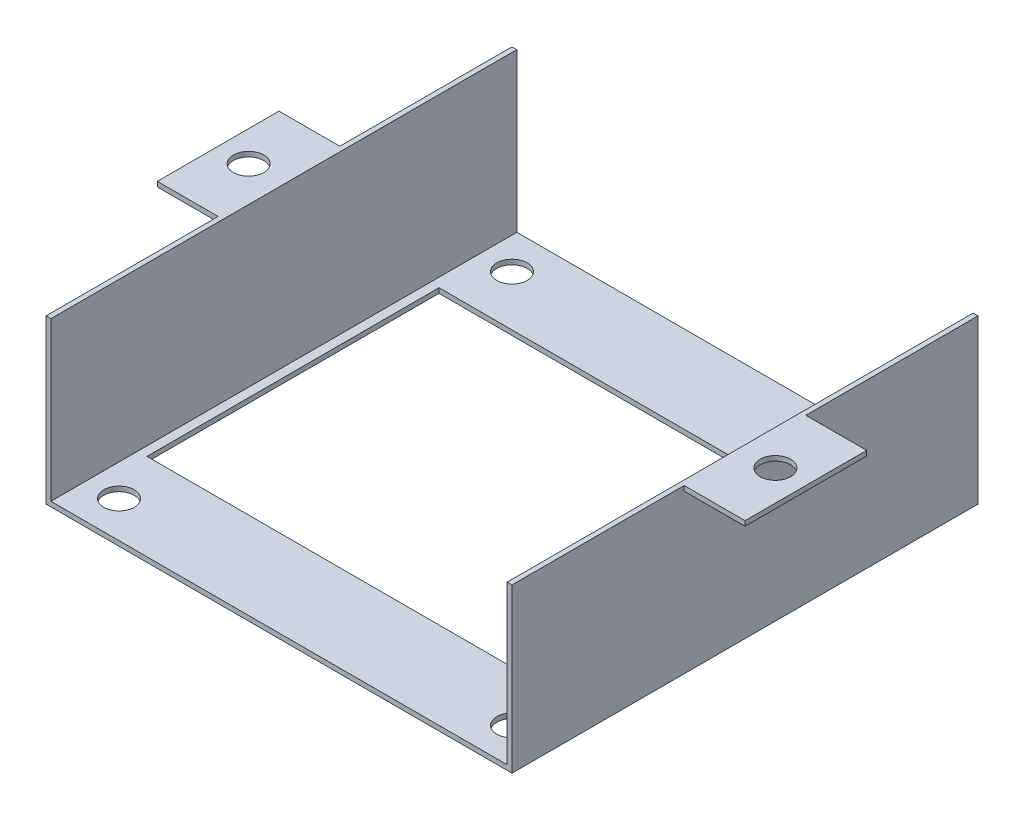
SolidWorks part; units mm, degrees
ref_plane "前视基准面" through (0, 0, 0) normal (0, 0, 1) x (1, 0, 0)
ref_plane "上视基准面" through (0, 0, 0) normal (0, 1, 0) x (1, 0, 0)
ref_plane "右视基准面" through (0, 0, 0) normal (1, 0, 0) x (0, 0, -1)
other "Configuration Table"
sketch "草图1" plane through (0, 0, 0) normal (0, 1, 0) x (1, 0, 0)
  line L0 (75, -37.5) -> (0, -37.5) construction
  line L1 (0, 0) -> (75, 0)
  line L2 (0, 0) -> (0, -75)
  line L3 (0, -75) -> (75, -75)
  line L4 (75, 0) -> (75, -75)
  line L6 (73.5, -37.5) -> (73.5, -13.5)
  line L10 (73.5, -13.5) -> (1.5, -13.5)
  line L11 (1.5, -13.5) -> (1.5, -61.5)
  line L12 (1.5, -61.5) -> (73.5, -61.5)
  line L13 (73.5, -61.5) -> (73.5, -37.5)
extrude "凸台-拉伸1" add sketch "草图1" along normal blind 0.8
sketch "草图2" plane through (0, 0, 0) normal (0, -1, 0) x (1, 0, 0)
  line L0 (75, 75) -> (75, 0) construction
  line L1 (0, 75) -> (75, 75)
  line L2 (0, 75) -> (0, 0)
  line L3 (0, 0) -> (75, 0)
  line L4 (75, 75) -> (75, 0)
  line L6 (-0.8, 75.8) -> (75.8, 75.8)
  line L7 (-0.8, 75.8) -> (-0.8, -0.8)
  line L8 (-0.8, -0.8) -> (75.8, -0.8)
  line L9 (75.8, 75.8) -> (75.8, -0.8)
  dimension "D1" = 0.8
  dimension "D2" = 0.8
  dimension "D3" = 0.8
  dimension "D4" = 0.8
extrude "凸台-拉伸2" add sketch "草图2" against normal blind 26.8
sketch "草图3" plane through (0, 26.8, 0) normal (0, 1, 0) x (1, 0, 0)
  line L0 (0, -37.5) -> (75, -37.5) construction
  line L3 (37.5, -37.5) -> (37.5, 0) construction
  line L5 (0, -27.5) -> (0, -47.5)
  line L17 (0, -75) -> (0, 0) construction
  line L18 (0, -27.5) -> (-10.8, -27.5)
  line L19 (-10.8, -27.5) -> (-10.8, -47.5)
  line L20 (0, -47.5) -> (-10.8, -47.5)
  line L21 (75, -47.5) -> (85.8, -47.5)
  line L22 (85.8, -27.5) -> (85.8, -47.5)
  line L23 (75, -27.5) -> (85.8, -27.5)
  line L24 (75, -27.5) -> (75, -47.5)
extrude "凸台-拉伸3" add sketch "草图3" against normal blind 0.8
hole_wizard "Ø5.0mm 暗销孔1" positions "草图4" profile "草图5" hole size "Ø5.0" standard "GB" end condition through all
sketch "草图4" plane through (0, 26.8, 0) normal (0, 1, 0) x (1, 0, 0)
  line L0 (0, -37.5) -> (75, -37.5) construction
  line L1 (0, 0) -> (0, -75) construction
  line L2 (75, 0) -> (75, -75) construction
  line L4 (37.5, 0) -> (37.5, -75) construction
  line L5 (75, 0) -> (0, 0) construction
  line L6 (0, -75) -> (75, -75) construction
  point P16 (-5.8, -37.5)
  point P20 (80.8, -37.5)
  dimension "D1" = 5.8
sketch "草图5" plane through (80.8, 26.8, 37.5) normal (1, 0, 0) x (0, 0, 1)
  line L0 (0, 0) -> (0, 26.8)
  line L1 (0, 26.8) -> (2.5, 26.8)
  line L2 (2.5, 26.8) -> (2.5, 0)
  line L5 (2.5, 0) -> (0, 0)
  line L11 (0, -6.35) -> (0, 107.95) construction
  dimension "通孔孔直径" = 5
  dimension "通孔孔深度" = 26.8
sketch "草图6" plane through (0, 0, 75.8) normal (0, 0, 1) x (1, 0, 0)
  line L0 (0, 26.8) -> (0, 0.8)
  line L1 (75.8, 26.8) -> (-0.8, 26.8) construction
  line L2 (0, 0.8) -> (75, 0.8)
  line L3 (75, 0.8) -> (75, 26.8)
  line L4 (75, 26.8) -> (0, 26.8)
  line L5 (-0.8, 26.8) -> (-0.8, 0) construction
  line L6 (75.8, 0) -> (-0.8, 0) construction
  line L7 (75.8, 26.8) -> (75.8, 0) construction
  dimension "D1" = 0.8
  dimension "D2" = 0.8
  dimension "D3" = 0.8
extrude "切除-拉伸1" cut sketch "草图6" against normal through all
hole_wizard "Ø5.0mm 暗销孔2" positions "草图7" profile "草图8" hole size "Ø5.0" standard "GB" end condition through all
sketch "草图7" plane through (0, 0, 0) normal (0, -1, 0) x (-1, 0, 0)
  line L0 (-37.5, 0.8) -> (-37.5, -75.8) construction
  line L1 (0.8, 0.8) -> (-75.8, 0.8) construction
  line L2 (-75.8, -75.8) -> (0.8, -75.8) construction
  line L4 (-75.8, -37.5) -> (0.8, -37.5) construction
  line L5 (-75.8, -27.5) -> (-75.8, -47.5) construction
  line L6 (0.8, -47.5) -> (0.8, -27.5) construction
  line L7 (-75.8, 0.8) -> (-75.8, -75.8) construction
  line L9 (0.8, -75.8) -> (0.8, 0.8) construction
  line L10 (-73.5, -61.5) -> (-73.5, -13.5) construction
  line L11 (-73.5, -13.5) -> (-1.5, -13.5) construction
  point P17 (-69.8, -5.2)
  point P28 (-5.2, -5.2)
  point P29 (-5.2, -69.8)
  point P30 (-69.8, -69.8)
  point P35 (0.8, -4.7138)
  dimension "D1" = 6
  dimension "D2" = 6
  dimension "D3" = 6
  dimension "D4" = 6
sketch "草图8" plane through (69.8, 0, 69.8) normal (1, 0, 0) x (0, 0, -1)
  line L0 (0, 0) -> (0, 26.8)
  line L1 (0, 26.8) -> (2.5, 26.8)
  line L2 (2.5, 26.8) -> (2.5, 0)
  line L5 (2.5, 0) -> (0, 0)
  line L11 (0, -6.35) -> (0, 107.95) construction
  dimension "通孔孔直径" = 5
  dimension "通孔孔深度" = 26.8
